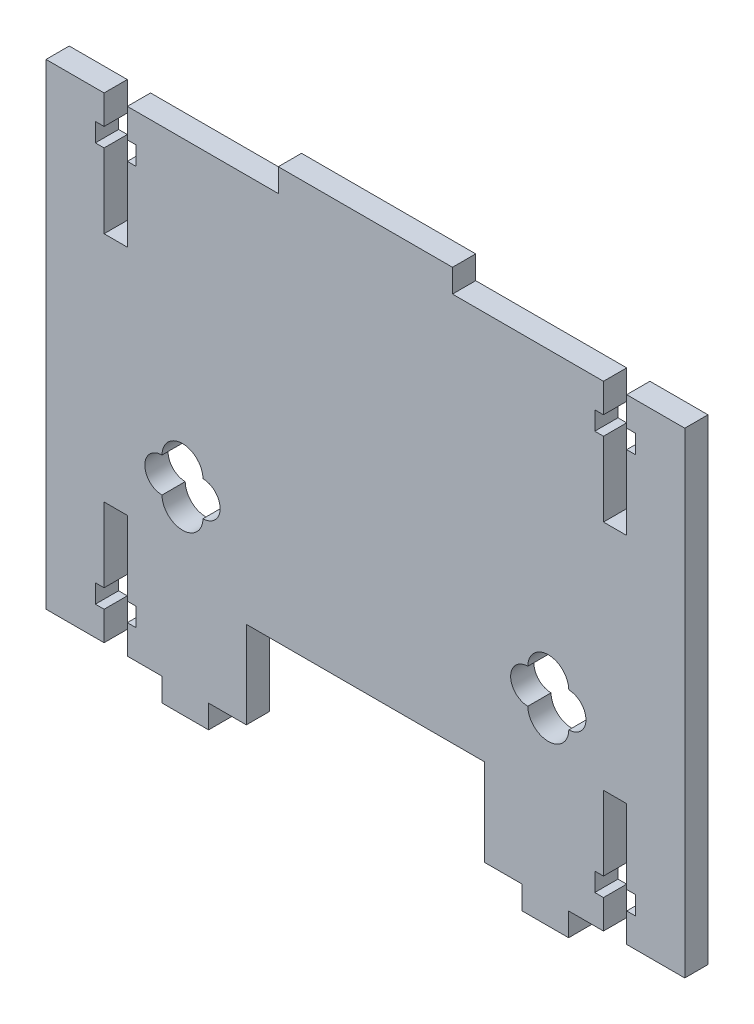
SolidWorks part; units mm, degrees
ref_plane "Front Plane" through (0, 0, 0) normal (0, 0, 1) x (1, 0, 0)
ref_plane "Top Plane" through (0, 0, 0) normal (0, 1, 0) x (1, 0, 0)
ref_plane "Right Plane" through (0, 0, 0) normal (1, 0, 0) x (0, 0, -1)
sketch "Sketch1" plane through (0, 0, 0) normal (0, 0, 1) x (1, 0, 0)
  line L0 (20.5, -41) -> (20.5, -26)
  line L1 (-55, 41) -> (-15, 41)
  line L2 (-55, 41) -> (-55, -41)
  line L3 (-55, -41) -> (-20.5, -41)
  line L4 (55, 41) -> (55, -41)
  line L5 (20.5, -26) -> (-20.5, -26)
  line L6 (-20.5, -26) -> (-20.5, -41)
  line L7 (20.5, -41) -> (55, -41)
  line L8 (15, 41) -> (15, 45)
  line L9 (15, 45) -> (-15, 45)
  line L10 (-15, 45) -> (-15, 41)
  line L11 (15, 41) -> (55, 41)
  dimension "D1" = 110
  dimension "D2" = 55
  dimension "D3" = 82
  dimension "D4" = 41
  dimension "D5" = 34.5
  dimension "D6" = 34.5
  dimension "D7" = 15
  dimension "D8" = 30
  dimension "D9" = 40
  dimension "D10" = 4
extrude "Boss-Extrude1" add sketch "Sketch1" along normal blind 4
sketch "Sketch2" plane through (0, 0, 0) normal (0, 0, -1) x (-1, 0, 0)
  line L0 (-43, -41) -> (-43, -26.1548) construction
  line L1 (-41, -36) -> (-41, -41)
  line L2 (-45, -32.8) -> (-45, -20)
  line L3 (-39.5, -32.8) -> (-41, -32.8)
  line L4 (-39.5, -36) -> (-39.5, -32.8)
  line L5 (-41, -36) -> (-39.5, -36)
  line L6 (-46.5, -32.8) -> (-45, -32.8)
  line L7 (-46.5, -36) -> (-46.5, -32.8)
  line L8 (-45, -36) -> (-46.5, -36)
  line L9 (-45, -41) -> (-41, -41)
  line L10 (-41, -20) -> (-41, -32.8)
  line L11 (-45, -20) -> (-41, -20)
  line L12 (-45, -41) -> (-45, -36)
  line L13 (-20.5, -41) -> (-55, -41) construction
  line L14 (-55, -41) -> (-55, 41) construction
  line L15 (0, 0) -> (0, -39.3618) construction
  line L16 (43, -41) -> (43, -26.1548) construction
  line L17 (45, -41) -> (45, -36)
  line L18 (45, -20) -> (41, -20)
  line L19 (41, -20) -> (41, -32.8)
  line L20 (45, -41) -> (41, -41)
  line L21 (45, -36) -> (46.5, -36)
  line L22 (46.5, -36) -> (46.5, -32.8)
  line L23 (46.5, -32.8) -> (45, -32.8)
  line L24 (41, -36) -> (39.5, -36)
  line L25 (39.5, -36) -> (39.5, -32.8)
  line L26 (39.5, -32.8) -> (41, -32.8)
  line L27 (45, -32.8) -> (45, -20)
  line L28 (41, -36) -> (41, -41)
  line L29 (0, 0) -> (24.2878, 0) construction
  line L30 (43, 41) -> (43, 26.1548) construction
  line L31 (41, 36) -> (41, 41)
  line L32 (45, 32.8) -> (45, 20)
  line L33 (39.5, 32.8) -> (41, 32.8)
  line L34 (39.5, 36) -> (39.5, 32.8)
  line L35 (41, 36) -> (39.5, 36)
  line L36 (46.5, 32.8) -> (45, 32.8)
  line L37 (46.5, 36) -> (46.5, 32.8)
  line L38 (45, 36) -> (46.5, 36)
  line L39 (45, 41) -> (41, 41)
  line L40 (41, 20) -> (41, 32.8)
  line L41 (45, 20) -> (41, 20)
  line L42 (45, 41) -> (45, 36)
  line L43 (-43, 41) -> (-43, 26.1548) construction
  line L44 (-45, 41) -> (-45, 36)
  line L45 (-45, 20) -> (-41, 20)
  line L46 (-41, 20) -> (-41, 32.8)
  line L47 (-45, 41) -> (-41, 41)
  line L48 (-45, 36) -> (-46.5, 36)
  line L49 (-46.5, 36) -> (-46.5, 32.8)
  line L50 (-46.5, 32.8) -> (-45, 32.8)
  line L51 (-41, 36) -> (-39.5, 36)
  line L52 (-39.5, 36) -> (-39.5, 32.8)
  line L53 (-39.5, 32.8) -> (-41, 32.8)
  line L54 (-45, 32.8) -> (-45, 20)
  line L55 (-41, 36) -> (-41, 41)
  dimension "D1" = 12.8
  dimension "D2" = 3.2
  dimension "D3" = 5
  dimension "D4" = 2
  dimension "D5" = 4
  dimension "D6" = 1.5
  dimension "D7" = 1.5
  dimension "D8" = 10
extrude "Cut-Extrude1" cut sketch "Sketch2" against normal blind 5
sketch "Sketch3" plane through (0, 0, 0) normal (0, 0, -1) x (-1, 0, 0)
  line L0 (0, 45) -> (0, -26.1863) construction
  line L1 (-15, 45) -> (15, 45) construction
  arc A4 (-27.9698, -8.0159) -> (-35.0302, -8.0159) centre (-31.5, -8.067) ccw
  arc A5 (-27.9698, -13.9841) -> (-27.9698, -8.0159) centre (-28, -11) ccw
  arc A6 (-35.0302, -13.9841) -> (-27.9698, -13.9841) centre (-31.5, -13.933) ccw
  arc A7 (-35.0302, -8.0159) -> (-35.0302, -13.9841) centre (-35, -11) ccw
  arc A8 (35.0302, -8.0159) -> (35.0302, -13.9841) centre (35, -11) cw
  arc A9 (35.0302, -13.9841) -> (27.9698, -13.9841) centre (31.5, -13.933) cw
  arc A10 (27.9698, -13.9841) -> (27.9698, -8.0159) centre (28, -11) cw
  arc A11 (27.9698, -8.0159) -> (35.0302, -8.0159) centre (31.5, -8.067) cw
extrude "Cut-Extrude2" cut sketch "Sketch3" against normal blind 10
sketch "Sketch4" plane through (0, 0, 0) normal (0, 0, -1) x (-1, 0, 0)
  line L0 (-20.5, -41) -> (-41, -41) construction
  line L1 (-35, -41) -> (-27, -41)
  line L2 (-35, -41) -> (-35, -45)
  line L3 (-35, -45) -> (-27, -45)
  line L4 (-27, -41) -> (-27, -45)
  line L5 (0, 0) -> (0, -44.9693) construction
  line L9 (-41, -41) -> (-41, -36) construction
  line L10 (27, -41) -> (27, -45)
  line L11 (35, -45) -> (27, -45)
  line L12 (35, -41) -> (35, -45)
  line L13 (35, -41) -> (27, -41)
  dimension "D1" = 4
  dimension "D2" = 8
  dimension "D3" = 6
extrude "Boss-Extrude2" add sketch "Sketch4" against normal blind 4
